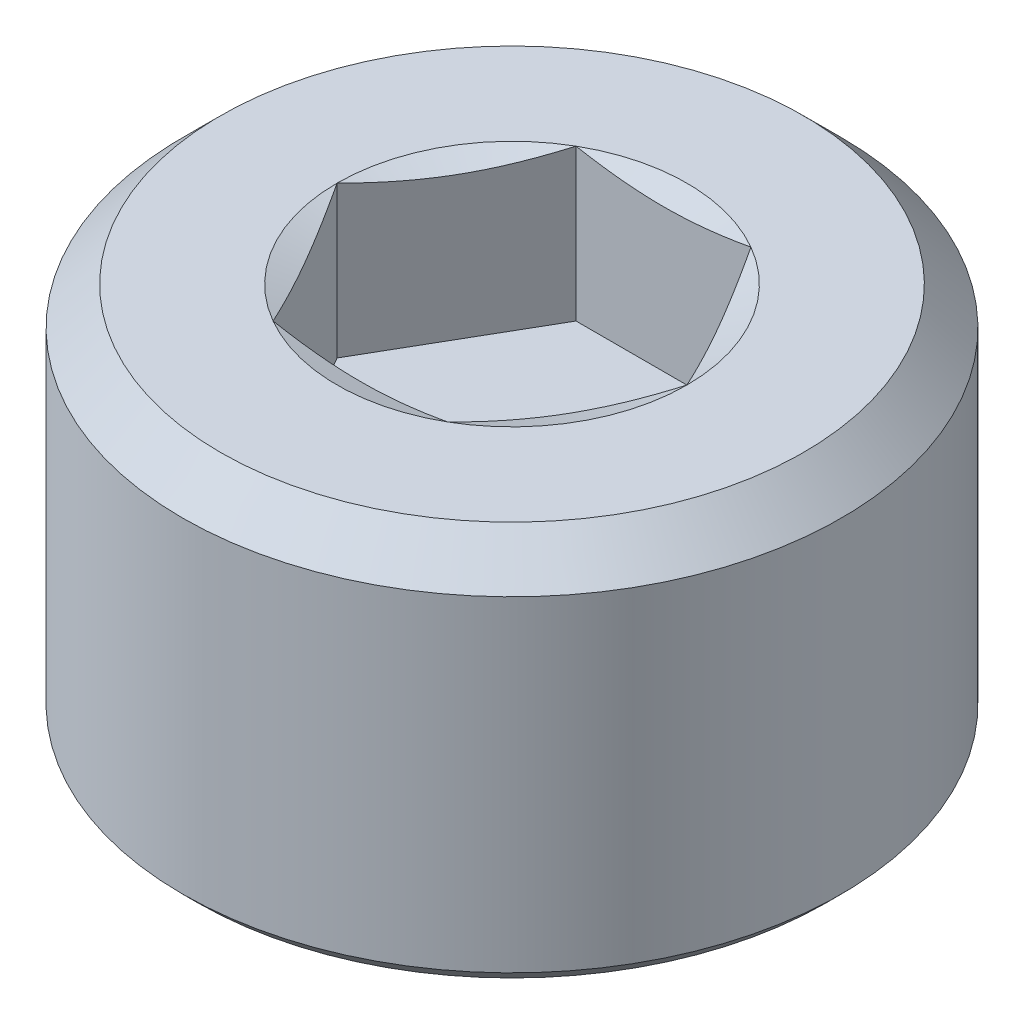
SolidWorks part; units mm, degrees
ref_plane "前视基准面" through (0, 0, 0) normal (0, 0, 1) x (1, 0, 0)
ref_plane "上视基准面" through (0, 0, 0) normal (0, 1, 0) x (1, 0, 0)
ref_plane "右视基准面" through (0, 0, 0) normal (1, 0, 0) x (0, 0, -1)
sketch "草图1" plane through (0, 0, 0) normal (0, 1, 0) x (1, 0, 0)
  circle A0 centre (0, 0) radius 4.35
  dimension "D1" = 8.7
extrude "凸台-拉伸1" add sketch "草图1" along normal blind 5
sketch "草图2" plane through (0, 5, 0) normal (0, 1, 0) x (1, 0, 0)
  line L1 (2.3094, 0) -> (1.1547, 2)
  line L2 (1.1547, 2) -> (-1.1547, 2)
  line L3 (-1.1547, 2) -> (-2.3094, 0)
  line L4 (-2.3094, 0) -> (-1.1547, -2)
  line L5 (-1.1547, -2) -> (1.1547, -2)
  line L6 (1.1547, -2) -> (2.3094, 0)
  circle A0 centre (0, 0) radius 2 construction
  dimension "D1" = 4
extrude "切除-拉伸1" cut sketch "草图2" against normal blind 2
sketch "草图3" plane through (0, 5, 0) normal (0, 1, 0) x (1, 0, 0)
  circle A0 centre (0, 0) radius 2.3094
ref_plane "基准面1" through (0, 4.7, 0) normal (0, 1, 0) x (1, 0, 0)
sketch "草图4" plane through (0, 4.7, 0) normal (0, 1, 0) x (1, 0, 0)
  circle A0 centre (0, 0) radius 1.5
loft "切除-放样1" cut profiles "草图3", "草图4"
chamfer "倒角1" distance 0.5 angle 45 1 edges at (0, 5, 4.35)
chamfer "倒角2" distance 0.2 angle 45 1 edges at (0, 0, 4.35)
